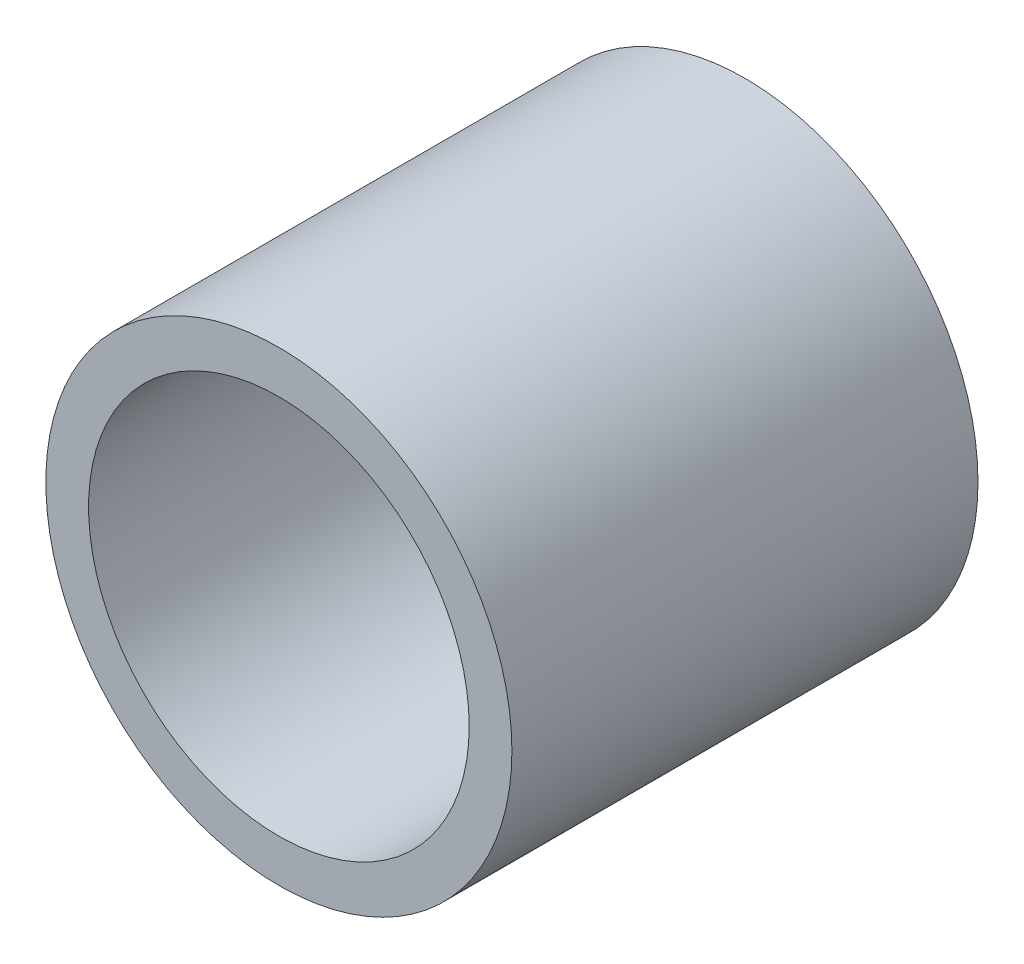
SolidWorks part; units mm, degrees
ref_plane "Front Plane" through (0, 0, 0) normal (0, 0, 1) x (1, 0, 0)
ref_plane "Top Plane" through (0, 0, 0) normal (0, 1, 0) x (1, 0, 0)
ref_plane "Right Plane" through (0, 0, 0) normal (1, 0, 0) x (0, 0, -1)
sketch "Sketch1" plane through (0, 0, 0) normal (0, 0, 1) x (1, 0, 0)
  circle A0 centre (0, 0) radius 60
  dimension "D1" = 120
extrude "Boss-Extrude1" add sketch "Sketch1" along normal blind 120
sketch "Sketch2" plane through (0, 0, 120) normal (0, 0, 1) x (1, 0, 0)
  circle A0 centre (0, 0) radius 49
  circle A1 centre (0, 0) radius 60 construction
  dimension "D1" = 11
extrude "Cut-Extrude1" cut sketch "Sketch2" against normal blind 130
